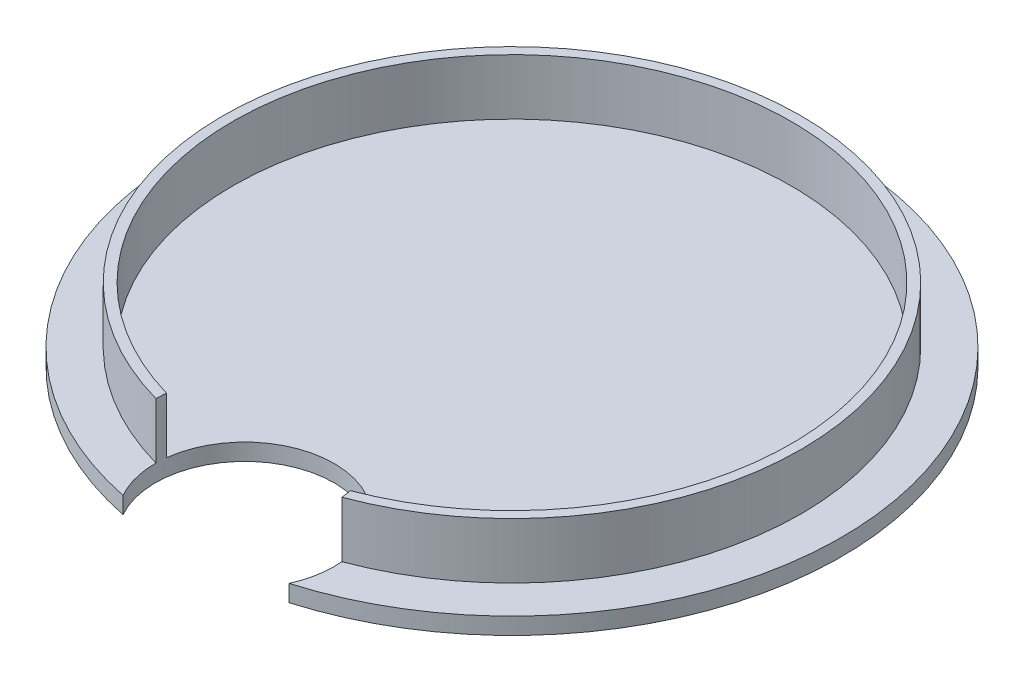
SolidWorks part; units mm, degrees
ref_plane "Front Plane" through (0, 0, 0) normal (0, 0, 1) x (1, 0, 0)
ref_plane "Top Plane" through (0, 0, 0) normal (0, 1, 0) x (1, 0, 0)
ref_plane "Right Plane" through (0, 0, 0) normal (1, 0, 0) x (0, 0, -1)
sketch "Sketch1" plane through (0, 0, 0) normal (0, 1, 0) x (1, 0, 0)
  circle A0 centre (0, 0) radius 59
extrude "Boss-Extrude1" add sketch "Sketch1" along normal blind 3
sketch "Sketch3" plane through (0, 3, 0) normal (0, 1, 0) x (1, 0, 0)
  circle A0 centre (0, 0) radius 51.75
extrude "Boss-Extrude2" add sketch "Sketch3" along normal blind 10
sketch "Sketch4" plane through (0, 13, 0) normal (0, 1, 0) x (1, 0, 0)
  circle A0 centre (0, 0) radius 50
extrude "Cut-Extrude2" cut sketch "Sketch4" against normal blind 10
sketch "Sketch6" plane through (0, 13, 0) normal (0, 1, 0) x (1, 0, 0)
  circle A0 centre (2.1104, -49.9554) radius 16
  circle A1 centre (0, 0) radius 50 construction
extrude "Cut-Extrude4" cut sketch "Sketch6" against normal blind 15
scale "Scale1" scale about centroid uniform scaling yes scale factor 0.5
